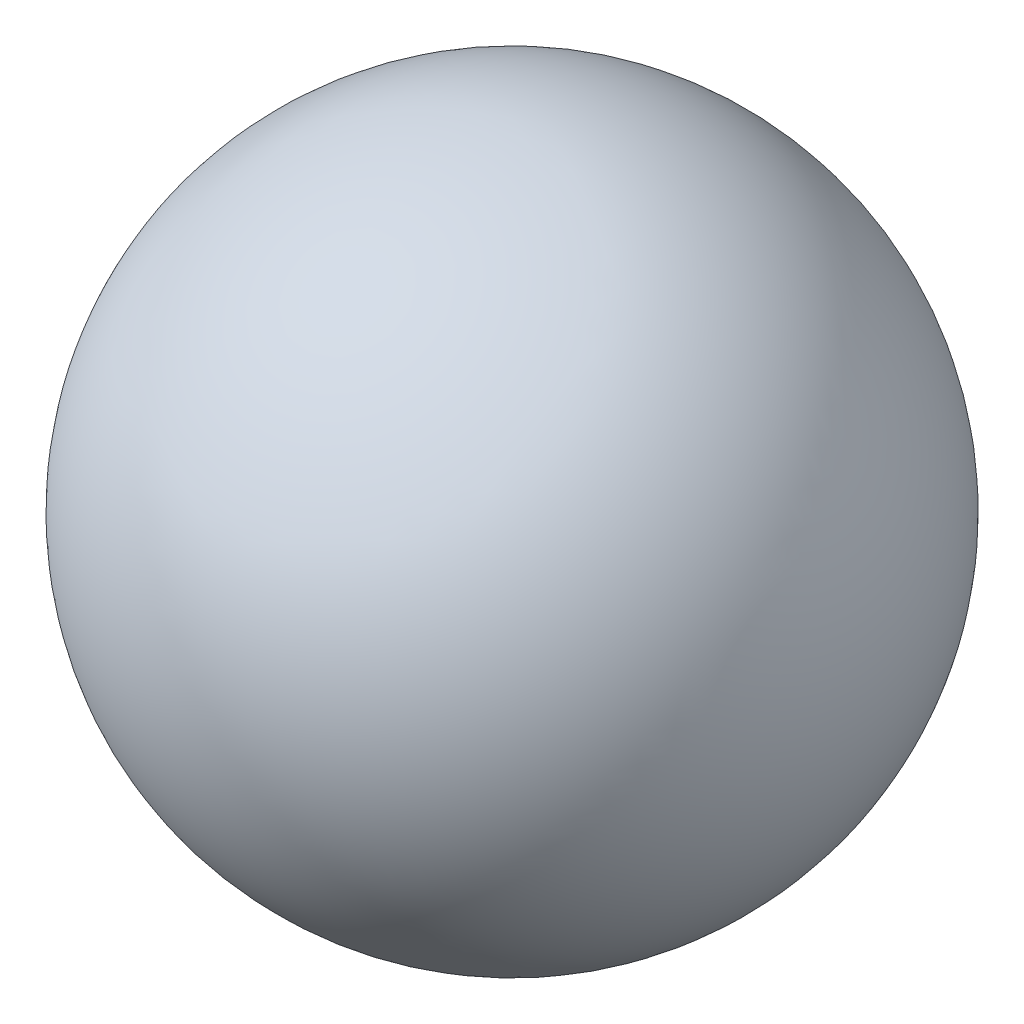
SolidWorks part; units mm, degrees
ref_plane "Front Plane" through (0, 0, 0) normal (0, 0, 1) x (1, 0, 0)
ref_plane "Top Plane" through (0, 0, 0) normal (0, 1, 0) x (1, 0, 0)
ref_plane "Right Plane" through (0, 0, 0) normal (1, 0, 0) x (0, 0, -1)
sketch "Sketch1" plane through (0, 0, 0) normal (0, 0, 1) x (1, 0, 0)
  line L0 (-40, 0) -> (40, 0)
  line L1 (-40, 0) -> (40, 0) construction
  arc A0 (40, 0) -> (-40, 0) centre (0, 0) ccw
revolve "Revolve1" add sketch "Sketch1" angle 360 about L1
